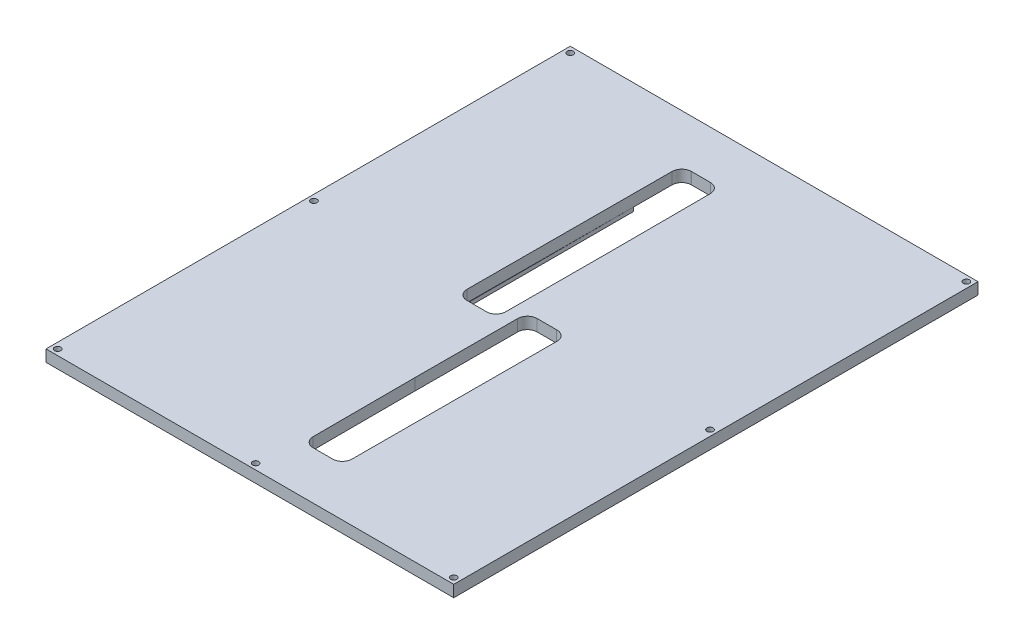
SolidWorks part; units mm, degrees
ref_plane "Front Plane" through (0, 0, 0) normal (0, 0, 1) x (1, 0, 0)
ref_plane "Top Plane" through (0, 0, 0) normal (0, 1, 0) x (1, 0, 0)
ref_plane "Right Plane" through (0, 0, 0) normal (1, 0, 0) x (0, 0, -1)
sketch "Sketch1" plane through (0, 0, 0) normal (0, 1, 0) x (1, 0, 0)
  line L0 (-23.9329, 105.348) -> (-24.1829, 0) construction
  line L1 (-24.1829, 0) -> (0, 0) construction
  line L2 (-17.9329, 105.348) -> (-18.1829, 0) construction
  line L3 (-12.9329, 105.3361) -> (-13.1829, -0.0119)
  line L8 (-22.9328, 105.3598) -> (-23.1828, 0.0119)
  line L10 (-105, -135) -> (105, -135)
  line L11 (23.9329, 105.348) -> (24.1829, 0) construction
  line L12 (18.9329, 105.3361) -> (19.1829, -0.0119) construction
  line L13 (28.9328, 105.3598) -> (29.1828, 0.0119) construction
  line L14 (17.9329, -105.3242) -> (18.1829, 0.0237) construction
  line L15 (12.9329, -105.3124) -> (13.1829, 0.0356)
  line L16 (22.9328, -105.3361) -> (23.1828, 0.0119)
  line L17 (-105, -135) -> (-105, 135)
  line L26 (-105, 135) -> (105, 135)
  line L27 (105, -135) -> (105, 135)
  line L28 (-105, -135) -> (105, 135) construction
  line L29 (-105, 135) -> (105, -135) construction
  arc A0 (-12.9329, 105.3361) -> (-22.9328, 105.3598) centre (-17.9329, 105.348) ccw
  arc A1 (-23.1828, 0.0119) -> (-13.1829, -0.0119) centre (-18.1829, 0) ccw
  arc A2 (18.9329, 105.3361) -> (28.9328, 105.3598) centre (23.9329, 105.348) cw construction
  arc A3 (29.1828, 0.0119) -> (19.1829, -0.0119) centre (24.1829, 0) cw construction
  arc A4 (12.9329, -105.3124) -> (22.9328, -105.3361) centre (17.9329, -105.3242) ccw
  arc A5 (23.1828, 0.0119) -> (13.1829, 0.0356) centre (18.1829, 0.0237) ccw
  point P7 (-18.0579, 52.674)
  point P18 (24.0579, 52.674)
  point P25 (18.0579, -52.6502)
  dimension "D1" = 270
  dimension "D2" = 210
extrude "Boss-Extrude1" add sketch "Sketch1" along normal blind 6
sketch "Sketch2" plane through (0, 6, 0) normal (0, 1, 0) x (-1, 0, 0)
  line L0 (41.4329, -85.6479) -> (41.4329, 97) construction
  line L1 (31.4329, -85.6479) -> (41.4329, -85.6479)
  line L2 (31.4329, -85.6479) -> (31.4329, 97)
  line L3 (31.4329, 97) -> (41.4329, 97)
  line L4 (41.4329, -85.6479) -> (41.4329, 97)
  line L5 (25.9329, 97) -> (15.9329, 97) construction
  line L6 (25.9329, -85.6479) -> (22.9796, -85.6479)
  line L7 (25.9329, -85.6479) -> (25.9329, 97)
  line L8 (25.9329, 97) -> (22.9796, 97)
  line L9 (22.9796, -85.6479) -> (22.9796, 97)
  line L11 (22.9328, -105.3598) -> (23.1828, -0.0119) construction
extrude "Boss-Extrude2" add sketch "Sketch2" against normal blind 2 from surface at -6 starting at face at (0, 0, 0)
mirror "Mirror1" about plane through (0, 0, 0) normal (1, 0, 0) of "Boss-Extrude2"
sketch "Sketch3" plane through (0, 0, 0) normal (0, -1, 0) x (1, 0, 0)
  line L4 (102, -132) -> (102, 132) construction
  line L5 (102, 132) -> (-102, 132) construction
  line L6 (-102, 132) -> (-102, -132) construction
  line L7 (-102, -132) -> (102, -132) construction
  line L12 (105, -135) -> (105, 135)
  line L13 (105, 135) -> (-105, 135)
  line L14 (-105, 135) -> (-105, -135)
  line L15 (-105, -135) -> (105, -135)
  line L16 (105, -135) -> (105, 135) construction
  line L17 (105, 135) -> (-105, 135) construction
  line L18 (-105, 135) -> (-105, -135) construction
  line L19 (-105, -135) -> (105, -135) construction
  circle A8 centre (-102, 132) radius 1.6
  circle A9 centre (0, 132) radius 1.6
  circle A10 centre (102, 132) radius 1.6
  circle A11 centre (-102, 0) radius 1.6
  circle A12 centre (-102, -132) radius 1.6
  circle A13 centre (102, -132) radius 1.6
  circle A14 centre (102, 0) radius 1.6
  dimension "D3" = 3.2
  dimension "D2" = 3
  dimension "D1" = 0
extrude "Cut-Extrude1" cut sketch "Sketch3" against normal blind 30
sketch "Sketch4" plane through (0, 0, 0) normal (0, -1, 0) x (1, 0, 0)
  line L0 (-8.1829, 5) -> (-18.1829, 5)
  line L1 (-3.1829, 0.0119) -> (-3.0578, -52.674)
  line L3 (-18.1829, 5) -> (-18.0519, -52.674)
  line L4 (-18.0519, -52.674) -> (-3.0578, -52.674) construction
  line L5 (-18.1829, -110.3479) -> (-18.0519, -52.674)
  line L6 (-3.1829, -105.3598) -> (-3.0578, -52.674)
  line L7 (-8.1829, -110.3479) -> (-18.1829, -110.3479)
  arc A0 (-13.1829, 0.0119) -> (-22.9796, 1.411) centre (-18.1829, 0) ccw construction
  arc A3 (-3.1829, 0.0119) -> (-8.1829, 5) centre (-8.1829, 0) ccw
  arc A4 (-3.1829, -105.3598) -> (-8.1829, -110.3479) centre (-8.1829, -105.3479) cw
extrude "Cut-Extrude2" cut sketch "Sketch4" against normal blind 10
sketch "Sketch5" plane through (0, 0, 0) normal (0, -1, 0) x (1, 0, 0)
  line L8 (17.7901, 52.6502) -> (2.796, 52.6502) construction
  line L9 (7.921, -5.0237) -> (17.921, -5.0237)
  line L10 (2.921, -0.0356) -> (2.796, 52.6502)
  line L11 (17.921, -5.0237) -> (17.7901, 52.6502)
  line L12 (17.921, 110.3242) -> (17.7901, 52.6502)
  line L13 (2.921, 105.3361) -> (2.796, 52.6502)
  line L14 (7.921, 110.3242) -> (17.921, 110.3242)
  arc A2 (2.921, -0.0356) -> (7.921, -5.0237) centre (7.921, -0.0237) ccw
  arc A3 (2.921, 105.3361) -> (7.921, 110.3242) centre (7.921, 105.3242) cw
  arc A4 (22.9328, 105.3361) -> (12.9329, 105.3124) centre (17.9329, 105.3242) ccw construction
  point P0 (17.921, 110.3242)
extrude "Cut-Extrude3" cut sketch "Sketch5" against normal blind 10
